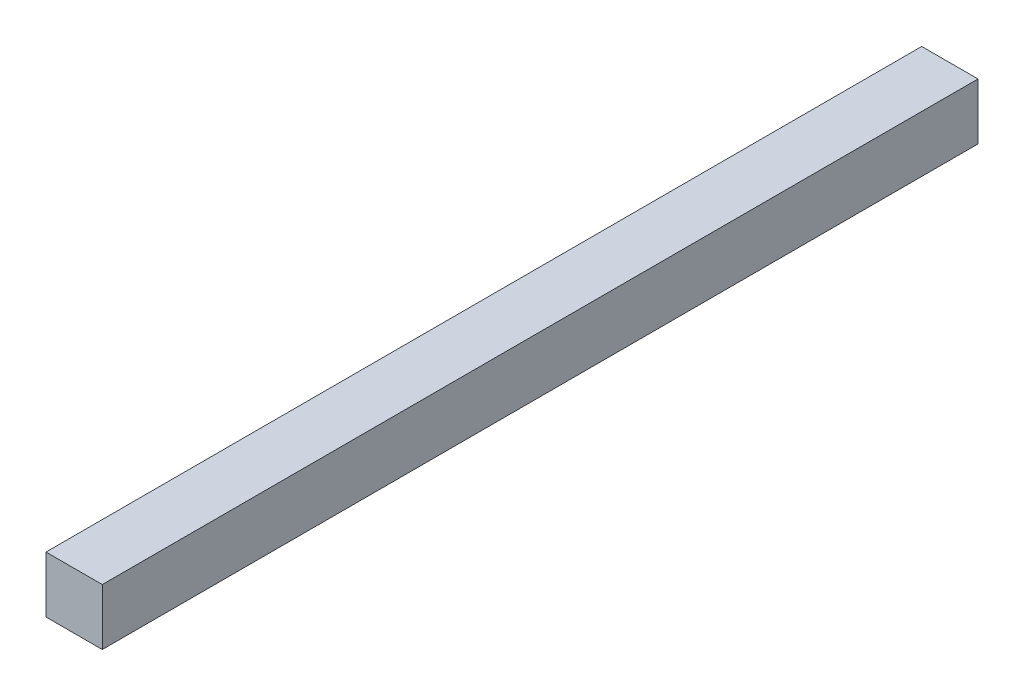
SolidWorks part; units mm, degrees
ref_plane "Front Plane" through (0, 0, 0) normal (0, 0, 1) x (1, 0, 0)
ref_plane "Top Plane" through (0, 0, 0) normal (0, 1, 0) x (1, 0, 0)
ref_plane "Right Plane" through (0, 0, 0) normal (1, 0, 0) x (0, 0, -1)
sketch "Sketch1" plane through (0, 0, 0) normal (0, 0, 1) x (1, 0, 0)
  line L1 (3.5355, -3.5355) -> (-3.5355, -3.5355)
  line L2 (3.5355, -3.5355) -> (3.5355, 3.5355)
  line L3 (3.5355, 3.5355) -> (-3.5355, 3.5355)
  line L4 (-3.5355, -3.5355) -> (-3.5355, 3.5355)
  line L5 (3.5355, -3.5355) -> (-3.5355, 3.5355) construction
  line L6 (3.5355, 3.5355) -> (-3.5355, -3.5355) construction
  circle A0 centre (0, 0) radius 5 construction
  dimension "D1" = 10
extrude "Boss-Extrude1" add sketch "Sketch1" along normal blind 110
